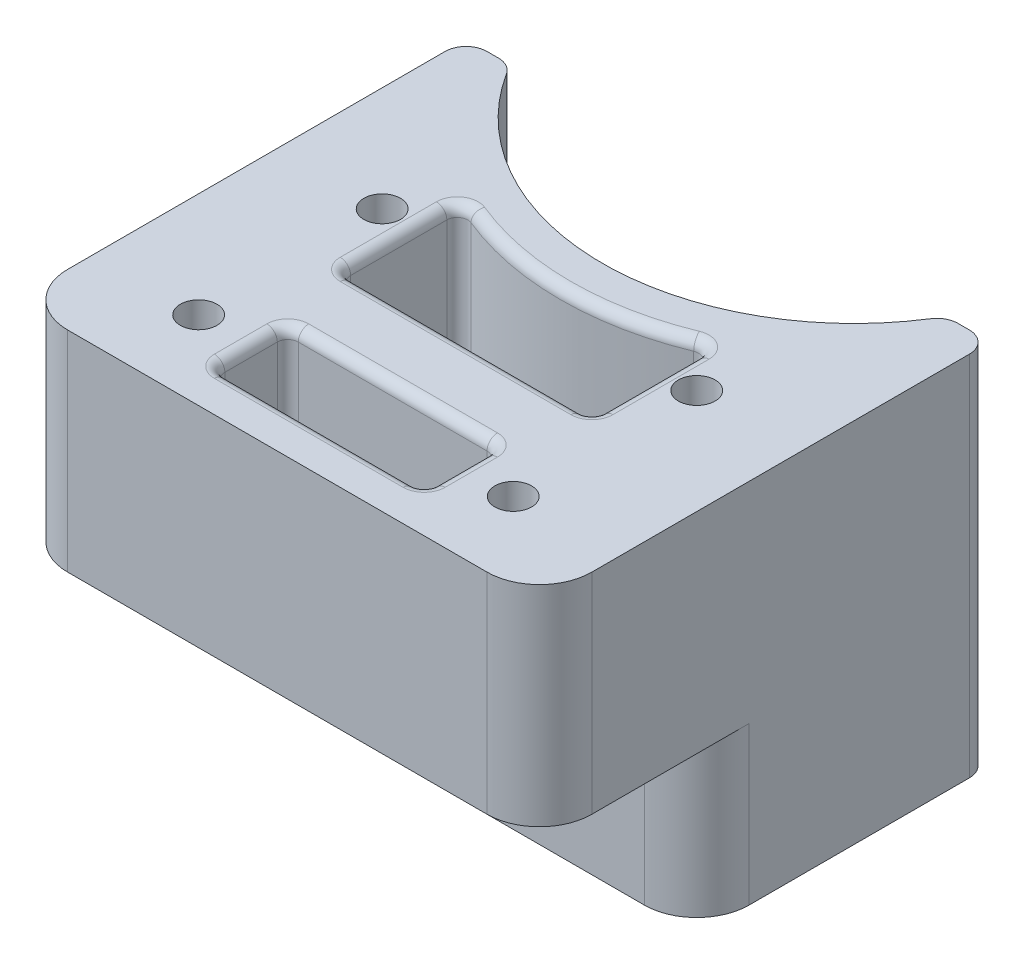
SolidWorks part; units mm, degrees
material "ABS"
ref_plane "前视基准面" through (0, 0, 0) normal (0, 0, 1) x (1, 0, 0)
ref_plane "上视基准面" through (0, 0, 0) normal (0, 1, 0) x (1, 0, 0)
ref_plane "右视基准面" through (0, 0, 0) normal (1, 0, 0) x (0, 0, -1)
other "Configuration Table"
sketch "草图1" plane through (0, 0, 0) normal (0, 1, 0) x (1, 0, 0)
  line L1 (-25, -25) -> (25, -25)
  line L2 (-25, -25) -> (-25, 25)
  line L3 (-25, 25) -> (25, 25)
  line L4 (25, -25) -> (25, 25)
  line L5 (-25, -25) -> (25, 25) construction
  line L6 (-25, 25) -> (25, -25) construction
  circle A0 centre (0, 0) radius 21.05
  dimension "D1" = 42.1
  dimension "D2" = 50
  dimension "D3" = 50
extrude "凸台-拉伸1" add sketch "草图1" along normal blind 15
sketch "草图2" plane through (0, 15, 0) normal (0, 1, 0) x (1, 0, 0)
  line L1 (-25, -40) -> (25, -40) construction
  line L2 (-25, -40) -> (-25, -55)
  line L3 (-25, -55) -> (25, -55)
  line L4 (25, -40) -> (25, -55)
  line L5 (-25, -47.5) -> (25, -47.5) construction
  line L6 (25, -25) -> (25, 25) construction
  line L7 (-25, -25) -> (25, -25)
  line L9 (-25, -40) -> (25, -40) construction
  line L11 (-25, -25) -> (25, -25)
  line L12 (-25, -25) -> (-25, -40)
  line L13 (-25, -40) -> (25, -40) construction
  line L14 (25, -25) -> (25, -40)
  circle A0 centre (-15, -47.5) radius 1.6
  circle A1 centre (15, -47.5) radius 1.6
  dimension "D2" = 3.2
  dimension "D3" = 3.2
  dimension "D4" = 10
  dimension "D1" = 15
  dimension "D5" = 10
  dimension "D6" = 40
extrude "凸台-拉伸2" add sketch "草图2" against normal up to surface (15 mm away)
fillet "圆角1" radius 3 4 edges at (25, 7.5, 55) (-25, 7.5, 55) (25, 7.5, -25) (-25, 7.5, -25)
sketch "草图3" plane through (0, 15, 0) normal (0, 1, 0) x (1, 0, 0)
  line L0 (0, 0) -> (0, -55) construction
  line L1 (-22, -55) -> (22, -55) construction
  line L2 (-15, -30) -> (15, -30) construction
  circle A0 centre (-15, -30) radius 1.75
  circle A1 centre (15, -30) radius 1.75
  dimension "D4" = 3.5
  dimension "D5" = 3.5
  dimension "D1" = 15
  dimension "D2" = 15
  dimension "D3" = 25
extrude "切除-拉伸1" cut sketch "草图3" against normal through all
sketch "草图4" plane through (0, 15, 0) normal (0, 1, 0) x (1, 0, 0)
  line L0 (-22, -55) -> (22, -55) construction
  line L1 (-31.3912, -40) -> (34.177, -40)
  line L2 (-31.3912, -40) -> (-31.3912, -60.4518)
  line L3 (-31.3912, -60.4518) -> (34.177, -60.4518)
  line L4 (34.177, -40) -> (34.177, -60.4518)
  line L11 (-32.2425, -12) -> (34.8543, -12)
  line L12 (-32.2425, -12) -> (-32.2425, 31.3532)
  line L13 (-32.2425, 31.3532) -> (34.8543, 31.3532)
  line L14 (34.8543, -12) -> (34.8543, 31.3532)
  circle A0 centre (0, 0) radius 24
  line M5 (-22, -55) -> (22, -55)
  arc M6 (22, -55) -> (25, -52) centre (22, -52) ccw
  line M7 (25, -52) -> (25, 22)
  arc M8 (25, 22) -> (22, 25) centre (22, 22) ccw
  line M9 (22, 25) -> (-22, 25)
  arc M10 (-22, 25) -> (-25, 22) centre (-22, 22) ccw
  line M11 (-25, 22) -> (-25, -52)
  arc M12 (-25, -52) -> (-22, -55) centre (-22, -52) ccw
  circle M13 centre (0, 0) radius 21.05
  circle M14 centre (15, -47.5) radius 1.6
  circle M15 centre (-15, -47.5) radius 1.6
  dimension "D2" = 48
  dimension "D1" = 15
  dimension "D3" = 28
extrude "切除-拉伸2" cut sketch "草图4" against normal through all contours L1 M11 M12 M5 M6 M7 M15 M14 | A0 L11 M7 M8 M9 M10 M11 | L11 A0 M13 | L11 A0 M13
sketch "草图5" plane through (0, 15, 0) normal (0, 1, 0) x (1, 0, 0)
  line L0 (-25, -47.5) -> (25, -47.5) construction
  line L1 (-25, -40) -> (25, -40)
  line L2 (-25, -40) -> (-25, -55)
  line L3 (-25, -55) -> (25, -55)
  line L4 (25, -40) -> (25, -55)
  line L5 (-25, -40) -> (25, -40)
  line L6 (25, -40) -> (25, -12)
  line L7 (25, -12) -> (20.7846, -12)
  line L8 (-20.7846, -12) -> (-25, -12)
  line L9 (-25, -12) -> (-25, -40)
  line L10 (-25, -40) -> (25, -40) construction
  line L11 (25, -40) -> (25, -12)
  line L12 (25, -12) -> (20.7846, -12)
  line L13 (-20.7846, -12) -> (-25, -12)
  line L14 (-25, -12) -> (-25, -40)
  circle A0 centre (-15, -30) radius 1.75 construction
  arc A1 (-20.7846, -12) -> (20.7846, -12) centre (0, 0) ccw
  arc A2 (-20.7846, -12) -> (20.7846, -12) centre (0, 0) ccw
  circle A3 centre (-15, -30) radius 1.75
  circle A4 centre (15, -30) radius 1.75 construction
  circle A5 centre (15, -30) radius 1.75
  circle A6 centre (-15, -47.5) radius 1.75
  circle A7 centre (15, -47.5) radius 1.75
  point P22 (0, -47.5)
  circle M7 centre (15, -30) radius 1.75
  circle M8 centre (-15, -30) radius 1.75
  line M9 (-25, -40) -> (25, -40)
  line M10 (25, -40) -> (25, -12)
  line M11 (25, -12) -> (20.7846, -12)
  arc M12 (20.7846, -12) -> (-20.7846, -12) centre (0, 0) cw
  line M13 (-20.7846, -12) -> (-25, -12)
  line M14 (-25, -12) -> (-25, -40)
  dimension "D3" = 3.5
  dimension "D4" = 3.5
  dimension "D6" = 15
  dimension "D2" = 15
  dimension "D5" = 15
  dimension "D1" = 0
extrude "凸台-拉伸3" add sketch "草图5" along normal blind 20 contours M14 M9 M10 M11 M12 M13 M8 M7 | L4 L2 L3 A7 A6 M9
fillet "圆角2" radius 2 4 edges at (-20.7846, 17.5, 12) (20.7846, 17.5, 12) (25, 17.5, 12) (-25, 17.5, 12)
fillet "圆角3" radius 5 4 edges at (-25, 25, 55) (-25, 7.5, 40) (25, 7.5, 40) (25, 25, 55)
sketch "草图6" plane through (0, 15, 0) normal (0, -1, 0) x (1, 0, 0)
  line L0 (0, 0) -> (0, 47.5) construction
  line L1 (-20, 55) -> (20, 55) construction
  line L3 (-10, 51) -> (10, 51)
  line L4 (-10, 51) -> (-10, 44)
  line L5 (-10, 44) -> (10, 44)
  line L6 (10, 51) -> (10, 44)
  line L7 (-10, 51) -> (10, 44) construction
  line L8 (-10, 44) -> (10, 51) construction
  dimension "D1" = 7.5
  dimension "D2" = 7
  dimension "D3" = 20
extrude "切除-拉伸3" cut sketch "草图6" against normal through all
sketch "草图7" plane through (0, 0, 0) normal (0, -1, 0) x (1, 0, 0)
  line L0 (0, 0) -> (0, 37) construction
  line L1 (0, 37) -> (-12, 37)
  line L2 (-12, 37) -> (-12, 25.2982)
  line L3 (0, 37) -> (12, 37)
  line L4 (12, 37) -> (12, 25.2982)
  line L5 (-20, 40) -> (20, 40) construction
  circle A0 centre (0, 0) radius 28
  dimension "D1" = 12
  dimension "D2" = 56
  dimension "D3" = 3
extrude "切除-拉伸4" cut sketch "草图7" against normal through all contours L0 A0 L4 L3 | A0 L0 L1 L2
fillet "圆角4" radius 1 24 edges at (-10, 35, 47.5) (-10, 15, 47.5) (10, 35, 47.5) (10, 15, 47.5) (0, 35, 37) (0, 0, 37) (0, 35, 28) (0, 0, 28) (10, 25, 51) (0, 35, 51) (-10, 25, 51) (0, 15, 51) (-10, 25, 44) (0, 35, 44) (10, 25, 44) (0, 15, 44) (12, 17.5, 25.2982) (12, 35, 31.1491) (12, 17.5, 37) (12, 0, 31.1491) (-12, 17.5, 37) (-12, 35, 31.1491) (-12, 17.5, 25.2982) (-12, 0, 31.1491)
